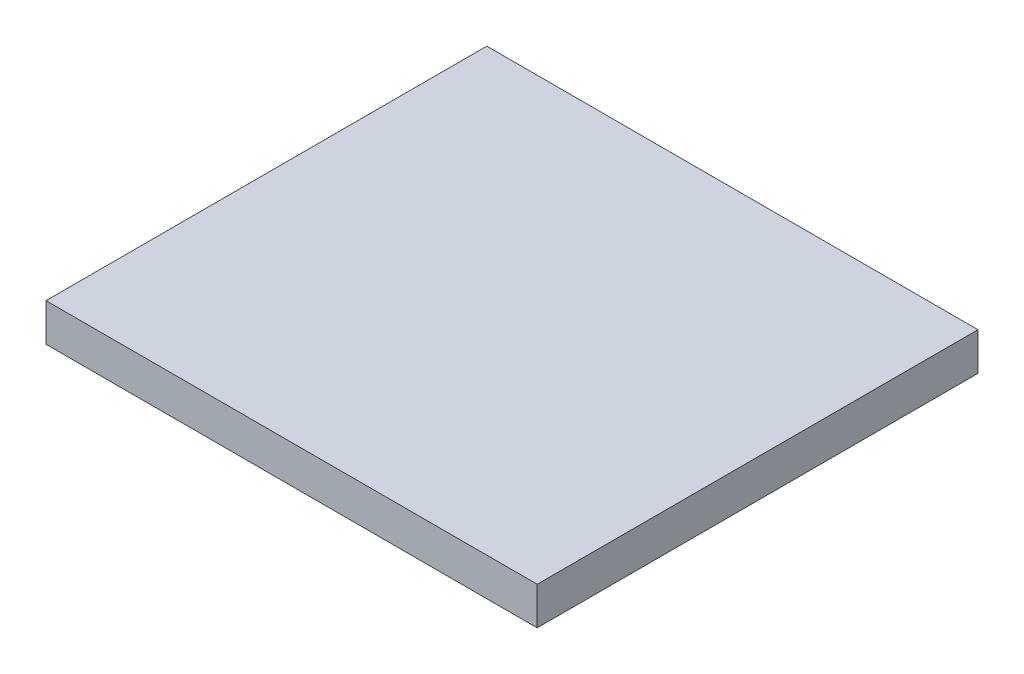
SolidWorks part; units mm, degrees
material "Acrylic (Medium-high impact)"
ref_plane "Front Plane" through (0, 0, 0) normal (0, 0, 1) x (1, 0, 0)
ref_plane "Top Plane" through (0, 0, 0) normal (0, 1, 0) x (1, 0, 0)
ref_plane "Right Plane" through (0, 0, 0) normal (1, 0, 0) x (0, 0, -1)
sketch "Sketch1" plane through (0, 0, 0) normal (0, 1, 0) x (1, 0, 0)
  line L10 (-189.9438, 52.5) -> (-111.9438, 52.5)
  line L11 (-189.9438, 52.5) -> (-189.9438, -17.5)
  line L12 (-189.9438, -17.5) -> (-111.9438, -17.5)
  line L13 (-111.9438, 52.5) -> (-111.9438, -17.5)
extrude "Boss-Extrude1" add sketch "Sketch1" along normal blind 6
